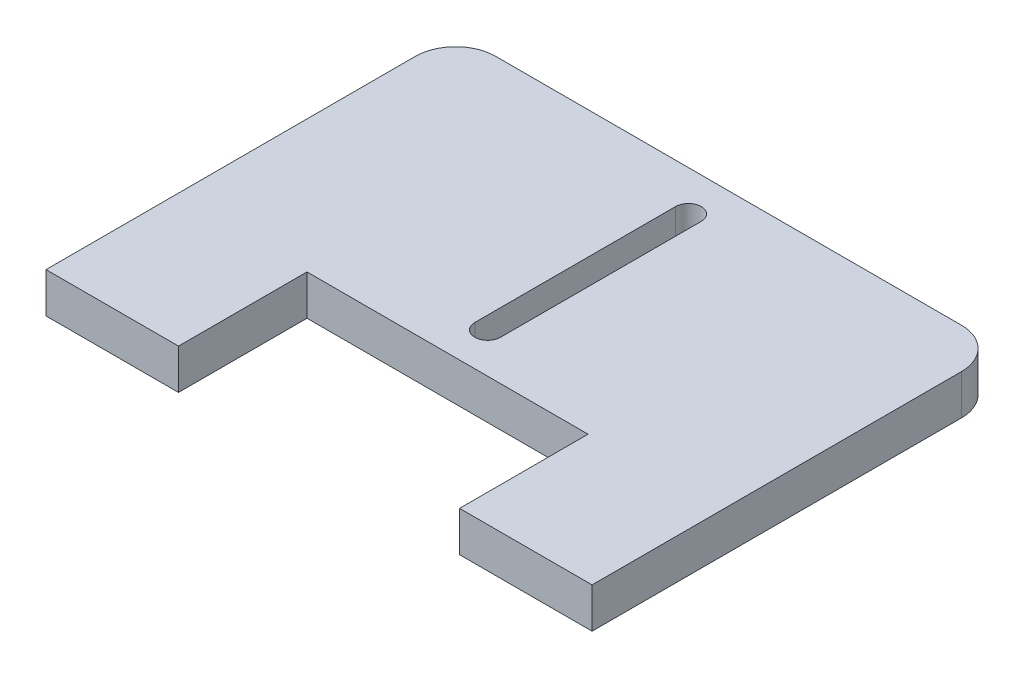
SolidWorks part; units mm, degrees
ref_plane "前视基准面" through (0, 0, 0) normal (0, 0, 1) x (1, 0, 0)
ref_plane "上视基准面" through (0, 0, 0) normal (0, 1, 0) x (1, 0, 0)
ref_plane "右视基准面" through (0, 0, 0) normal (1, 0, 0) x (0, 0, -1)
other "Configuration Table"
sketch "草图1" plane through (0, 0, 0) normal (0, 1, 0) x (1, 0, 0)
  line L0 (0, 0) -> (0, -32022.2036) construction
  line L1 (0, 0) -> (-32022.2036, 0) construction
  line L2 (30, 22.8491) -> (-30, 22.8491)
  line L3 (-30, 22.8491) -> (-30, -5.1509)
  line L4 (-30, -5.1509) -> (-34, -5.1509)
  line L5 (-34, -5.1509) -> (-34, -28.1509)
  line L6 (-34, -28.1509) -> (-17.5, -28.1509)
  line L7 (-17.5, -28.1509) -> (-17.5, -12.1509)
  line L8 (-17.5, -12.1509) -> (17.5, -12.1509)
  line L9 (17.5, -28.1509) -> (17.5, -12.1509)
  line L10 (34, -28.1509) -> (17.5, -28.1509)
  line L11 (34, -5.1509) -> (34, -28.1509)
  line L12 (30, -5.1509) -> (34, -5.1509)
  line L13 (30, 22.8491) -> (30, -5.1509)
  line L14 (0, 17.8491) -> (0, -7.1509) construction
  line L15 (1.6, 17.8491) -> (1.6, -7.1509)
  line L16 (-1.6, 17.8491) -> (-1.6, -7.1509)
  arc A0 (1.6, 17.8491) -> (-1.6, 17.8491) centre (0, 17.8491) ccw
  arc A1 (-1.6, -7.1509) -> (1.6, -7.1509) centre (0, -7.1509) ccw
  point P15 (0, -12.1509)
  point P19 (0, 22.8491)
  point P21 (0, 5.3491)
  dimension "D7" = 1.6
  dimension "D1" = 28
  dimension "D2" = 60
  dimension "D3" = 34
  dimension "D4" = 35
  dimension "D5" = 16
  dimension "D6" = 35
  dimension "D8" = 5
  dimension "D9" = 5
extrude "凸台-拉伸1" add sketch "草图1" along normal blind 5
sketch "草图2" plane through (0, 0, 0) normal (0, 1, 0) x (1, 0, 0)
  line L0 (-30, 22.8491) -> (-34, 22.8491)
  line L1 (-34, -5.1509) -> (-34, 22.8491)
  line L2 (34, -5.1509) -> (34, 22.8491)
  line L3 (34, 22.8491) -> (30, 22.8491)
  line L4 (-30, 22.8491) -> (-30, -5.1509)
  line L5 (-30, -5.1509) -> (-34, -5.1509)
  line L6 (30, 22.8491) -> (30, -5.1509)
  line L7 (34, -5.1509) -> (30, -5.1509) construction
  line L8 (30, -5.1509) -> (34, -5.1509)
extrude "凸台-拉伸2" add sketch "草图2" along normal blind 5
fillet "圆角1" radius 5 2 edges at (34, 2.5, -22.8491) (-34, 2.5, -22.8491)
